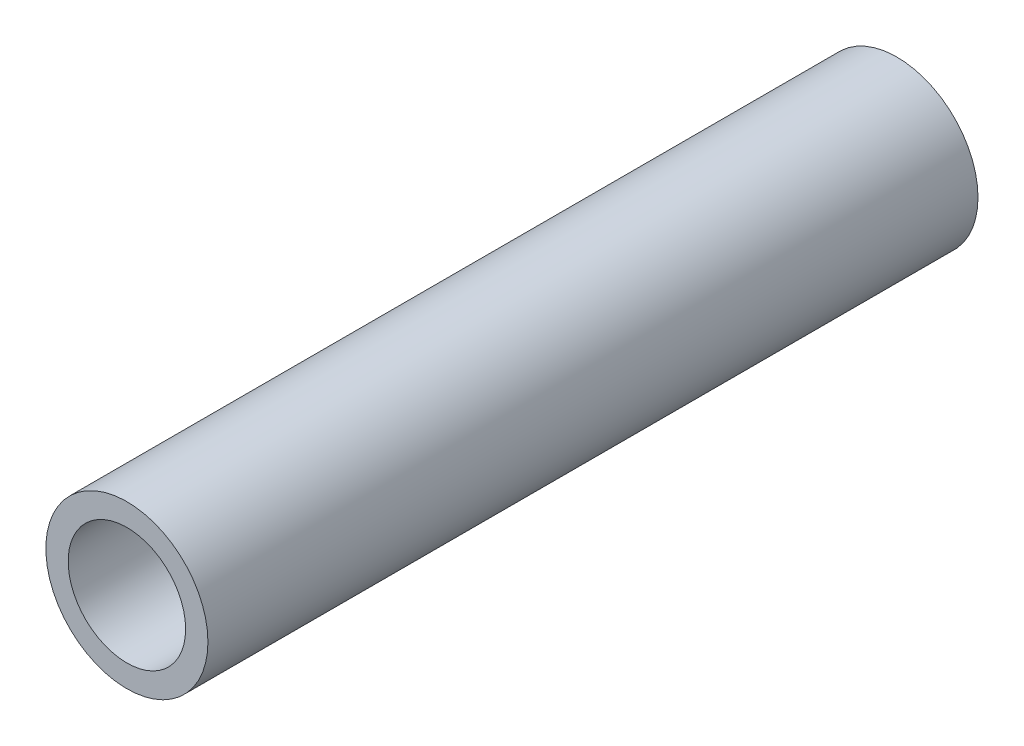
SolidWorks part; units mm, degrees
ref_plane "Front Plane" through (0, 0, 0) normal (0, 0, 1) x (1, 0, 0)
ref_plane "Top Plane" through (0, 0, 0) normal (0, 1, 0) x (1, 0, 0)
ref_plane "Right Plane" through (0, 0, 0) normal (1, 0, 0) x (0, 0, -1)
sketch "Sketch1" plane through (0, 0, 0) normal (0, 0, 1) x (1, 0, 0)
  circle A0 centre (0, 0) radius 10.6934
  circle A1 centre (0, 0) radius 7.747
  dimension "D1" = 21.3868
  dimension "D2" = 15.494
extrude "Boss-Extrude1" add sketch "Sketch1" along normal blind 101.6
